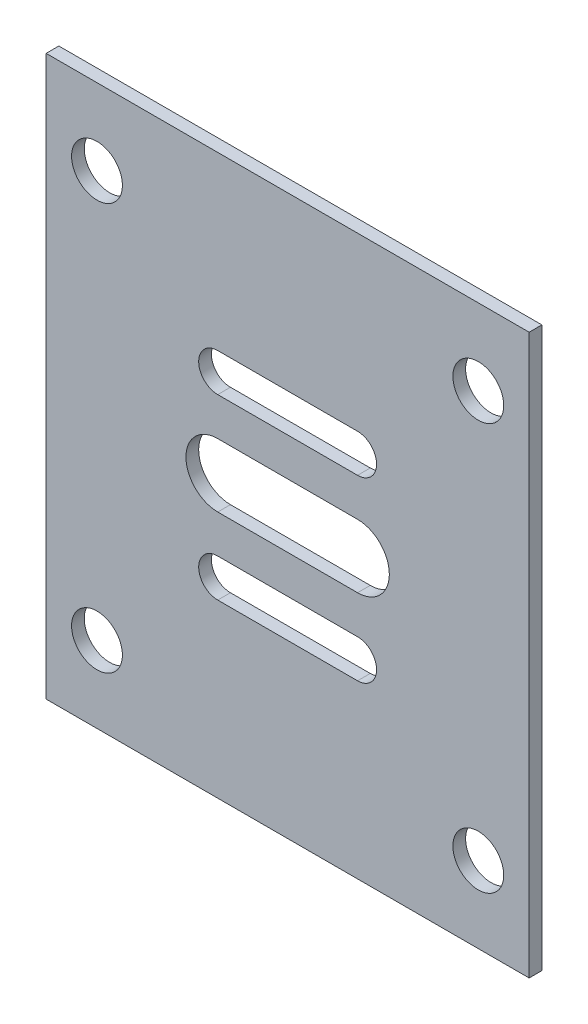
SolidWorks part; units mm, degrees
ref_plane "Front Plane" through (0, 0, 0) normal (0, 0, 1) x (1, 0, 0)
ref_plane "Top Plane" through (0, 0, 0) normal (0, 1, 0) x (1, 0, 0)
ref_plane "Right Plane" through (0, 0, 0) normal (1, 0, 0) x (0, 0, -1)
sketch "Sketch1" plane through (0, 0, 0) normal (0, 0, 1) x (1, 0, 0)
  line L0 (0, 22) -> (61.3846, 22) construction
  line L1 (0, 0) -> (38, 0)
  line L2 (0, 0) -> (0, 44)
  line L3 (0, 44) -> (38, 44)
  line L4 (38, 0) -> (38, 44)
  line L5 (13.5, 22) -> (24.5, 22) construction
  line L6 (13.5, 24.5) -> (24.5, 24.5)
  line L7 (13.5, 19.5) -> (24.5, 19.5)
  line L8 (13.5, 29) -> (24.5, 29) construction
  line L9 (13.5, 30.5) -> (24.5, 30.5)
  line L10 (13.5, 27.5) -> (24.5, 27.5)
  line L11 (13.5, 15) -> (24.5, 15) construction
  line L12 (13.5, 16.5) -> (24.5, 16.5)
  line L13 (13.5, 13.5) -> (24.5, 13.5)
  circle A0 centre (4, 38) radius 2
  circle A1 centre (34, 38) radius 2
  circle A2 centre (34, 6) radius 2
  circle A3 centre (4, 6) radius 2
  arc A4 (13.5, 24.5) -> (13.5, 19.5) centre (13.5, 22) ccw
  arc A5 (24.5, 19.5) -> (24.5, 24.5) centre (24.5, 22) ccw
  arc A6 (13.5, 30.5) -> (13.5, 27.5) centre (13.5, 29) ccw
  arc A7 (24.5, 27.5) -> (24.5, 30.5) centre (24.5, 29) ccw
  arc A8 (13.5, 16.5) -> (13.5, 13.5) centre (13.5, 15) ccw
  arc A9 (24.5, 13.5) -> (24.5, 16.5) centre (24.5, 15) ccw
  point P17 (19, 22)
  point P22 (19, 29)
  point P29 (19, 15)
  point P36 (19, 44)
  dimension "D3" = 4
  dimension "D11" = 4
  dimension "D12" = 4
  dimension "D13" = 4
  dimension "D14" = 4
  dimension "D15" = 3
  dimension "D1" = 38
  dimension "D2" = 44
  dimension "D4" = 6
  dimension "D5" = 6
  dimension "D6" = 4
  dimension "D7" = 6
  dimension "D8" = 4
  dimension "D9" = 6
  dimension "D10" = 4
  dimension "D16" = 3
  dimension "D17" = 5
  dimension "D18" = 3
  dimension "D19" = 3
  dimension "D20" = 11
  dimension "D21" = 11
  dimension "D22" = 11
extrude "Boss-Extrude1" add sketch "Sketch1" along normal blind 1
